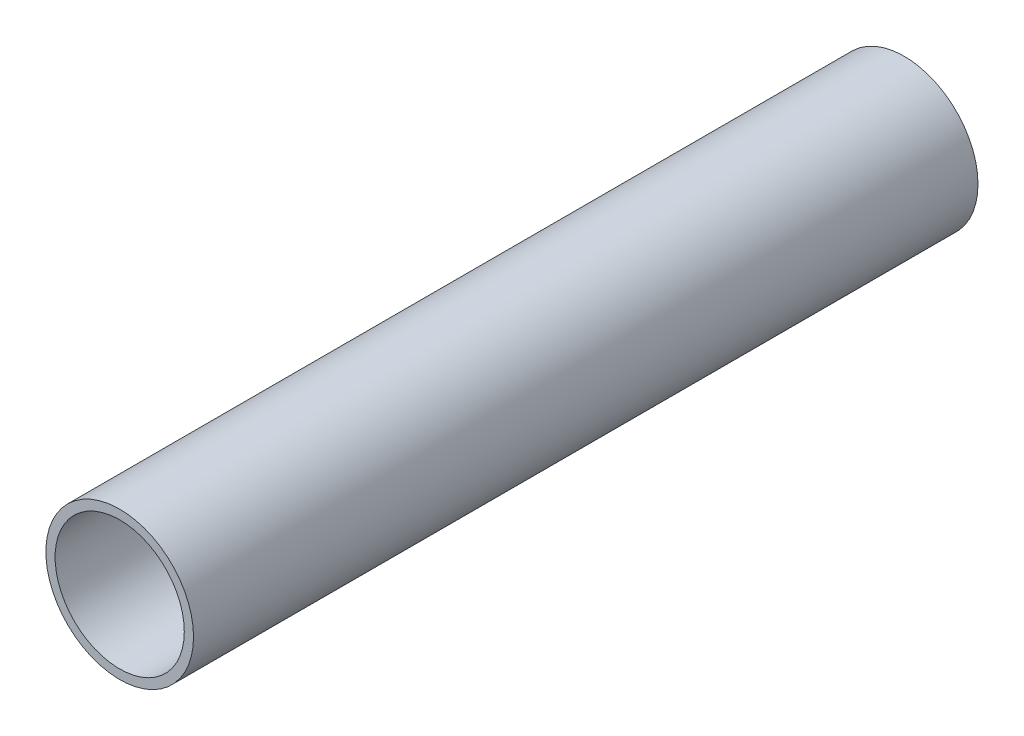
SolidWorks part; units mm, degrees
material "cf"
ref_plane "Front Plane" through (0, 0, 0) normal (0, 0, 1) x (1, 0, 0)
ref_plane "Top Plane" through (0, 0, 0) normal (0, 1, 0) x (1, 0, 0)
ref_plane "Right Plane" through (0, 0, 0) normal (1, 0, 0) x (0, 0, -1)
sketch "Sketch1" plane through (0, 0, 0) normal (0, 0, 1) x (1, 0, 0)
  circle A0 centre (0, 0) radius 8
  circle A1 centre (0, 0) radius 7
  dimension "D1" = 16
  dimension "D2" = 14
extrude "Boss-Extrude1" add sketch "Sketch1" along normal blind 85
